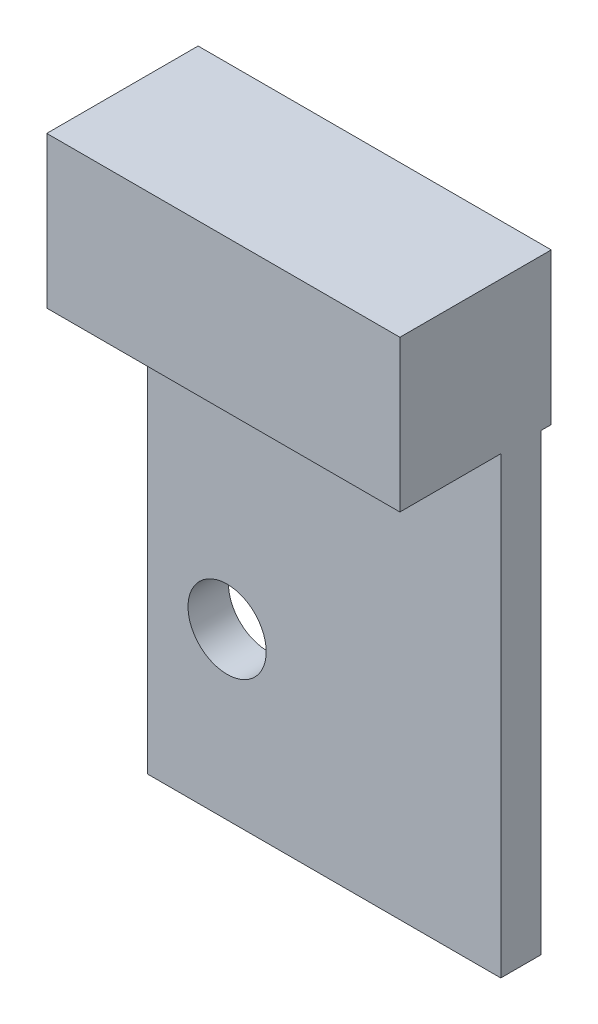
SolidWorks part; units mm, degrees
ref_plane "Front Plane" through (0, 0, 0) normal (0, 0, 1) x (1, 0, 0)
ref_plane "Top Plane" through (0, 0, 0) normal (0, 1, 0) x (1, 0, 0)
ref_plane "Right Plane" through (0, 0, 0) normal (1, 0, 0) x (0, 0, -1)
sketch "Sketch1" plane through (0, 0, 0) normal (0, 0, 1) x (1, 0, 0)
  line L1 (-7, 9) -> (7, 9)
  line L2 (-7, 9) -> (-7, -9)
  line L3 (-7, -9) -> (7, -9)
  line L4 (7, 9) -> (7, -9)
  line L5 (-7, 9) -> (7, -9) construction
  line L6 (-7, -9) -> (7, 9) construction
  point P0 (0, 0)
  dimension "D1" = 14
  dimension "D2" = 18
extrude "Boss-Extrude1" add sketch "Sketch1" along normal blind 1.6
sketch "Sketch2" plane through (0, 0, 1.6) normal (0, 0, 1) x (1, 0, 0)
  line L0 (7, 9) -> (-7, 9) construction
  line L1 (-7, 15) -> (7, 15)
  line L2 (-7, 15) -> (-7, 9)
  line L3 (-7, 9) -> (7, 9)
  line L4 (7, 15) -> (7, 9)
  line L5 (-7, -9) -> (7, -9) construction
  point P4 (0, 9)
  point P7 (0, 9)
  dimension "D1" = 6
extrude "Boss-Extrude2" add sketch "Sketch2" along normal blind 6 from offset 2 offset against normal yes
sketch "Sketch3" plane through (0, 0, 1.6) normal (0, 0, 1) x (1, 0, 0)
  line L0 (-7, 9) -> (-7, -9) construction
  line L1 (-7, -9) -> (7, -9) construction
  circle A0 centre (-3.85, -2.45) radius 1.55
  dimension "D1" = 3.1
  dimension "D2" = 3.15
  dimension "D3" = 6.55
extrude "Cut-Extrude1" cut sketch "Sketch3" against normal through all
